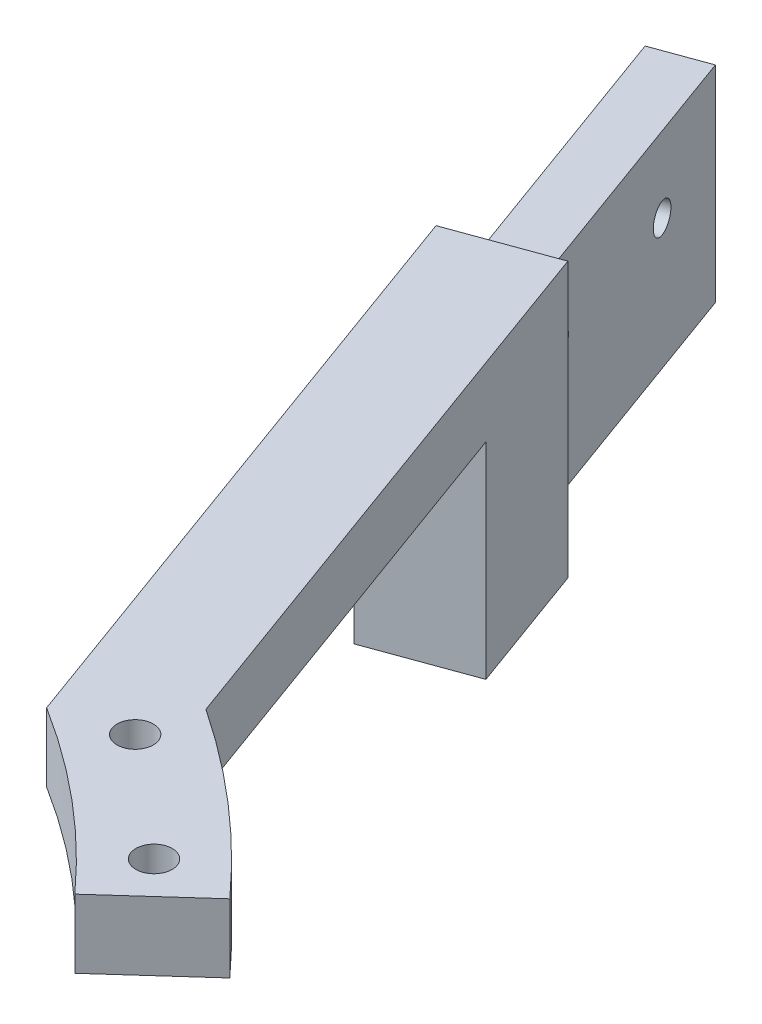
SolidWorks part; units mm, degrees
ref_plane "前视基准面" through (0, 0, 0) normal (0, 0, 1) x (1, 0, 0)
ref_plane "上视基准面" through (0, 0, 0) normal (0, 1, 0) x (1, 0, 0)
ref_plane "右视基准面" through (0, 0, 0) normal (1, 0, 0) x (0, 0, -1)
other "Configuration Table"
sketch "草图1" plane through (0, 0, 0) normal (0, 1, 0) x (1, 0, 0)
  line L0 (0, 0) -> (73.4178, 104.8515) construction
  line L5 (0, 0) -> (119, 0) construction
  line L6 (0, 0) -> (90.5097, 90.5097) construction
  line L9 (63.5903, 101.7658) -> (0, 0) construction
  line L17 (63.5903, 101.7658) -> (31.0984, 191.0366)
  line L18 (31.0984, 191.0366) -> (45.1938, 196.1669)
  line L19 (45.1938, 196.1669) -> (75.3957, 113.1879)
  line L20 (0, 0) -> (89.1774, 80.2957) construction
  line L21 (89.1774, 80.2957) -> (101.0677, 91.0018)
  arc A1 (107.8018, 82.9142) -> (75.3957, 113.1879) centre (0, 0) ccw
  circle A3 centre (73.4178, 104.8515) radius 2.65
  arc A5 (101.0677, 91.0018) -> (75.3957, 113.1879) centre (0, 0) ccw
  arc A8 (98.9122, 67.9439) -> (63.5903, 101.7658) centre (0, 0) ccw construction
  arc A9 (89.1774, 80.2957) -> (63.5903, 101.7658) centre (0, 0) ccw
  circle A10 centre (90.5097, 90.5097) radius 2.65
  arc A11 (95.1225, 85.6487) -> (59.3532, 113.4072) centre (0, 0) ccw construction
  point P11 (0, 0)
  dimension "D1" = 5.3
  dimension "D2" = 15
  dimension "D5" = 136
  dimension "D6" = 42
  dimension "D8" = 5.3
  dimension "D10" = 120
  dimension "D12" = 256
  dimension "D3" = 55
  dimension "D4" = 10
  dimension "D7" = 95
  dimension "D9" = 58
  dimension "D11" = 128
extrude "凸台-拉伸3" add sketch "草图1" along normal blind 10
ref_plane "基准面1" through (75.3957, 10, -113.1879) normal (0, -1, 0) x (-1, 0, 0)
sketch "草图14" plane through (0, 0, 0) normal (0, -1, 0) x (1, 0, 0)
  line L0 (45.1938, -196.1669) -> (31.0984, -191.0366)
  line L1 (31.0984, -191.0366) -> (37.9388, -172.2427)
  line L2 (63.5903, -101.7658) -> (31.0984, -191.0366) construction
  line L3 (37.9388, -172.2427) -> (52.0342, -177.373)
  line L4 (45.1938, -196.1669) -> (75.3957, -113.1879) construction
  line L5 (52.0342, -177.373) -> (45.1938, -196.1669)
  dimension "D1" = 20
extrude "凸台-拉伸4" add sketch "草图14" along normal blind 30
sketch "草图15" plane through (-57.7601, 0, -158.6947) normal (-0.342, 0, -0.9397) x (-0.9397, 0, 0.342)
  line L0 (-109.5613, 10) -> (-109.5613, -30) construction
  line L1 (-94.5613, -30) -> (-109.5613, -30)
  line L2 (-94.5613, -30) -> (-94.5613, 0)
  line L3 (-94.5613, 0) -> (-109.5613, 0)
  line L4 (-109.5613, -30) -> (-109.5613, 0)
  dimension "D1" = 30
extrude "凸台-拉伸5" add sketch "草图15" along normal blind 51 separate body contours L2 L1 L4 L3
sketch "草图16" plane through (102.9539, 0, -37.4722) normal (0.9397, 0, -0.342) x (-0.342, 0, -0.9397)
  line L0 (219.8794, 0) -> (206.8794, 0) construction
  line L1 (219.8794, 0) -> (168.8794, 0) construction
  line L2 (206.8794, 0) -> (206.8794, -11) construction
  line L3 (206.8794, -11) -> (181.8794, -11) construction
  circle A0 centre (206.8794, -11) radius 2.15
  circle A1 centre (181.8794, -11) radius 2.15
  dimension "D4" = 4.3
  dimension "D5" = 4.3
  dimension "D1" = 13
  dimension "D2" = 25
  dimension "D3" = 11
extrude "切除-拉伸6" cut sketch "草图16" against normal through all
sketch "草图17" plane through (102.9539, 0, -37.4722) normal (0.9397, 0, -0.342) x (-0.342, 0, -0.9397)
  line L4 (168.8794, 0) -> (168.8794, -30)
  line L5 (168.8794, -30) -> (219.8794, -30)
  line L6 (219.8794, -30) -> (219.8794, 0)
  line L7 (219.8794, 0) -> (168.8794, 0)
  line L8 (168.8794, 0) -> (168.8794, -30)
  line L9 (168.8794, -30) -> (219.8794, -30)
  line L10 (219.8794, -30) -> (219.8794, 0)
  line L11 (219.8794, 0) -> (168.8794, 0)
  dimension "D1" = 0
extrude "切除-拉伸7" cut sketch "草图17" against normal blind 7
